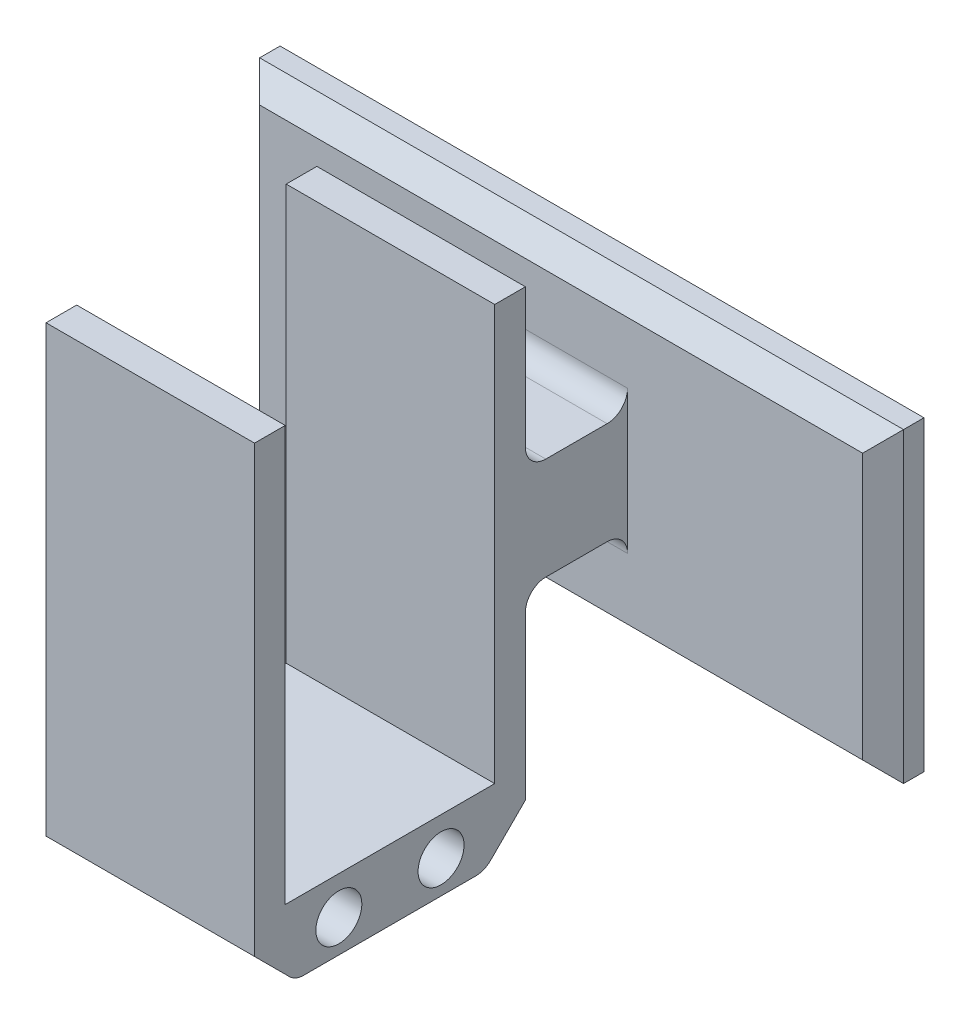
SolidWorks part; units mm, degrees
material "PLA"
ref_plane "Front Plane" through (0, 0, 0) normal (0, 0, 1) x (1, 0, 0)
ref_plane "Top Plane" through (0, 0, 0) normal (0, 1, 0) x (1, 0, 0)
ref_plane "Right Plane" through (0, 0, 0) normal (1, 0, 0) x (0, 0, -1)
sketch "Sketch1" plane through (0, 0, 0) normal (1, 0, 0) x (0, 0, -1)
  line L0 (-10.25, 20.3) -> (10.25, 20.3)
  line L1 (-10.25, -20.3) -> (10.25, -20.3)
  line L2 (-10.25, -20.3) -> (-10.25, 20.3)
  line L4 (10.25, -20.3) -> (10.25, 20.3)
  line L5 (-10.25, -20.3) -> (-13.25, -20.3)
  line L6 (-13.25, -20.3) -> (-13.25, 29.7)
  line L7 (-13.25, 29.7) -> (13.25, 29.7)
  line L8 (10.25, -20.3) -> (13.25, -20.3)
  line L11 (-10.05, 20.1) -> (10.05, 20.1)
  line L13 (13.25, -20.3) -> (13.25, 29.7)
  point P5 (0, 20.3)
  point P6 (-10.25, 0)
  line B0 (-8.8772, 20.1) -> (-10.8742, 20.1) construction
  line B1 (7.4, 20.1) -> (11.2713, 20.1) construction
  line B2 (10.05, 18.0597) -> (10.05, 22.3295) construction
  line B3 (-3.2, -20.1) -> (-12.1258, -20.1) construction
  line B4 (-10.05, -15.1145) -> (-10.05, -21.3251) construction
  line B5 (-10.05, -20.1) -> (10.05, -20.1)
  line B6 (-10.05, -20.1) -> (-10.05, 20.1)
  line B7 (10.05, -20.1) -> (10.05, 20.1)
  circle B8 centre (-5, 24) radius 2.25
  circle B9 centre (5, 24) radius 2.25
  dimension "D1" = 0.2
  dimension "D2" = 0.2
  dimension "D3" = 0.2
  dimension "D4" = 0.2
  dimension "D5" = 3
  dimension "D6" = 50
  dimension "D7" = 3
sketch_block_instance "Block1-1"
sketch_block "Block1"
extrude "Boss-Extrude1" add sketch "Sketch1" along normal blind 20 contours L8 L13 L7 L6 L5 L2 L0 L4 B9 B8
sketch "Sketch2" plane through (0, 0, 0) normal (-1, 0, 0) x (0, 0, 1)
  circle A0 centre (-5, 24) radius 2.25
  circle A1 centre (5, 24) radius 2.25
extrude "Boss-Extrude2" add sketch "Sketch2" against normal blind 10
sketch "Sketch4" plane through (20, 0, 0) normal (1, 0, 0) x (0, 0, -1)
  line L0 (13.25, -20.3) -> (13.25, 29.7) construction
  line L1 (-13.25, 29.7) -> (13.25, 29.7)
  line L2 (-13.25, 29.7) -> (-13.25, 27.2)
  line L3 (-13.25, 27.2) -> (13.25, 27.2)
  line L4 (13.25, 29.7) -> (13.25, 27.2)
  dimension "D1" = 2.5
extrude "Cut-Extrude1" cut sketch "Sketch4" against normal through all
chamfer "Chamfer2" distance 4 angle 45 1 edges at (10, 27.2, -13.25)
chamfer "Chamfer3" distance 4 angle 45 1 edges at (10, 27.2, 13.25)
fillet "Fillet4" radius 2 2 edges at (10, 27.2, -9.25) (10, 27.2, 9.25)
sketch "Sketch7" plane through (20, 0, 0) normal (1, 0, 0) x (0, 0, -1)
  line L0 (13.25, -20.3) -> (13.25, 23.2) construction
  line L3 (23.25, -5.3) -> (13.25, -5.3)
  line L6 (13.25, 4.7) -> (23.25, 4.7)
  line L8 (23.25, 4.7) -> (23.25, -5.3)
  line L9 (13.25, 4.7) -> (13.25, -5.3)
  line L10 (10.25, -20.3) -> (13.25, -20.3) construction
  dimension "D1" = 10
  dimension "D2" = 15
extrude "Boss-Extrude5" add sketch "Sketch7" against normal up to surface (20 mm away) up to face at (0, 9.4758, 0)
fillet "Fillet6" radius 2 2 edges at (10, 4.7, -13.25) (10, -5.3, -13.25)
sketch "Sketch8" plane through (0, 0, -23.25) normal (0, 0, -1) x (-1, 0, 0)
  line L1 (-45.4, 14.7) -> (17.6, 14.7)
  line L2 (-45.4, 14.7) -> (-45.4, -15.3)
  line L3 (-45.4, -15.3) -> (17.6, -15.3)
  line L4 (17.6, 14.7) -> (17.6, -15.3)
  line L5 (0, 4.7) -> (-20, 4.7) construction
  line L7 (-13.9, 4.7) -> (-13.9, -5.3) construction
  line L8 (-20, -5.3) -> (-20, 4.7) construction
  line L9 (-20, -0.3) -> (0, -0.3) construction
  line L10 (0, 4.7) -> (0, -5.3) construction
  line L11 (0, -5.3) -> (-20, -5.3) construction
  point P10 (-13.9, 14.7)
  point P17 (-45.4, -0.3)
  dimension "D1" = 63
  dimension "D2" = 30
  dimension "D3" = 6.1
extrude "Boss-Extrude6" add sketch "Sketch8" along normal blind 4
chamfer "Chamfer4" distance 2 angle 45 4 edges at (-17.6, -0.3, -23.25) (13.9, -15.3, -23.25) (45.4, -0.3, -23.25) (13.9, 14.7, -23.25)
fillet "Fillet7" radius 2 2 edges at (10, 4.7, -23.25) (10, -5.3, -23.25)
ref_plane "Plane2" through (20, 20.3, 10.25) normal (0, 0, -1) x (-1, 0, 0)
sketch "Sketch12" plane through (20, 0, 0) normal (1, 0, 0) x (0, 0, -1)
  line L0 (13.25, 23.2) -> (9.8358, 26.6142) construction
  line L1 (-8.4216, 27.2) -> (8.4216, 27.2) construction
  line L2 (-9.8358, 26.6142) -> (-13.25, 23.2) construction
  line L3 (13.25, 23.2) -> (9.8358, 26.6142)
  line L4 (-8.4216, 27.2) -> (8.4216, 27.2)
  line L5 (-9.8358, 26.6142) -> (-13.25, 23.2)
  line L6 (0, 20.3) -> (-13.25, 20.3) construction
  line L7 (-10.25, 20.3) -> (10.25, 20.3) construction
  line L8 (-13.25, -20.3) -> (-13.25, 23.2) construction
  line L9 (-13.25, 20.3) -> (13.25, 20.3)
  line L10 (13.25, 6.7) -> (13.25, 23.2) construction
  line L11 (13.25, 20.3) -> (13.25, 23.2)
  line L12 (-13.25, 20.3) -> (-13.25, 23.2)
  arc A0 (9.8358, 26.6142) -> (8.4216, 27.2) centre (8.4216, 25.2) ccw construction
  arc A1 (-8.4216, 27.2) -> (-9.8358, 26.6142) centre (-8.4216, 25.2) ccw construction
  arc A2 (9.8358, 26.6142) -> (8.4216, 27.2) centre (8.4216, 25.2) ccw
  arc A3 (-8.4216, 27.2) -> (-9.8358, 26.6142) centre (-8.4216, 25.2) ccw
sketch "Sketch13" plane through (20, 0, 0) normal (1, 0, 0) x (0, 0, -1)
  line B0 (-13.25, -23.2) -> (-9.8358, -26.6142)
  line B1 (8.4216, -27.2) -> (-8.4216, -27.2)
  line B2 (9.8358, -26.6142) -> (13.25, -23.2)
  line B3 (0, -20.3) -> (13.25, -20.3) construction
  line B4 (13.25, -20.3) -> (-13.25, -20.3)
  line B5 (-13.25, -20.3) -> (-13.25, -23.2)
  line B6 (13.25, -20.3) -> (13.25, -23.2)
  arc B7 (-9.8358, -26.6142) -> (-8.4216, -27.2) centre (-8.4216, -25.2) ccw
  arc B8 (8.4216, -27.2) -> (9.8358, -26.6142) centre (8.4216, -25.2) ccw
  circle B9 centre (5, -24) radius 2.25
  circle B10 centre (-5, -24) radius 2.25
sketch_block_instance "Block2-1"
sketch_block "Block2"
extrude "Boss-Extrude8" add sketch "Sketch13" against normal up to surface (20 mm away) up to face at (0, 5.5655, -7.3)
extrude "Cut-Extrude2" cut sketch "Sketch12" against normal through all
sketch "Sketch14" plane through (0, 0, 0) normal (-1, 0, 0) x (0, 0, 1)
  circle A0 centre (-5, -24) radius 2.25
  circle A1 centre (5, -24) radius 2.25
extrude "Boss-Extrude9" add sketch "Sketch14" against normal blind 10
sketch "Sketch15" plane through (20, 0, 0) normal (1, 0, 0) x (0, 0, -1)
  line L14 (-10.25, 20.3) -> (-13.25, 20.3)
  line L15 (-13.25, 20.3) -> (-13.25, -23.2)
  line L16 (-13.25, -23.2) -> (-9.8358, -26.6142)
  line L17 (-8.4216, -27.2) -> (8.4216, -27.2)
  line L18 (9.8358, -26.6142) -> (13.25, -23.2)
  line L19 (13.25, -23.2) -> (13.25, -7.3)
  line L20 (15.25, -5.3) -> (21.25, -5.3)
  line L21 (23.25, -7.3) -> (23.25, 6.7)
  line L22 (21.25, 4.7) -> (15.25, 4.7)
  line L23 (13.25, 6.7) -> (13.25, 20.3)
  line L24 (13.25, 20.3) -> (10.25, 20.3)
  line L25 (10.25, 20.3) -> (10.25, -20.3)
  line L26 (10.25, -20.3) -> (-10.25, -20.3)
  line L27 (-10.25, -20.3) -> (-10.25, 20.3)
  line L28 (-10.25, 20.3) -> (-13.25, 20.3)
  line L29 (-13.25, 20.3) -> (-13.25, -23.2)
  line L30 (-13.25, -23.2) -> (-9.8358, -26.6142)
  line L31 (-8.4216, -27.2) -> (8.4216, -27.2)
  line L32 (9.8358, -26.6142) -> (13.25, -23.2)
  line L33 (13.25, -23.2) -> (13.25, -7.3)
  line L34 (15.25, -5.3) -> (21.25, -5.3)
  line L35 (23.25, -7.3) -> (23.25, 6.7)
  line L36 (21.25, 4.7) -> (15.25, 4.7)
  line L37 (13.25, 6.7) -> (13.25, 20.3)
  line L38 (13.25, 20.3) -> (10.25, 20.3)
  line L39 (10.25, 20.3) -> (10.25, -20.3)
  line L40 (10.25, -20.3) -> (-10.25, -20.3)
  line L41 (-10.25, -20.3) -> (-10.25, 20.3)
  circle A0 centre (5, -24) radius 2.25 construction
  circle A1 centre (-5, -24) radius 2.25 construction
  circle A2 centre (5, -24) radius 2.25
  circle A3 centre (-5, -24) radius 2.25
  arc A6 (-9.8358, -26.6142) -> (-8.4216, -27.2) centre (-8.4216, -25.2) ccw
  arc A7 (8.4216, -27.2) -> (9.8358, -26.6142) centre (8.4216, -25.2) ccw
  arc A8 (15.25, -5.3) -> (13.25, -7.3) centre (15.25, -7.3) ccw
  arc A9 (23.25, -7.3) -> (21.25, -5.3) centre (21.25, -7.3) ccw
  arc A10 (21.25, 4.7) -> (23.25, 6.7) centre (21.25, 6.7) ccw
  arc A11 (13.25, 6.7) -> (15.25, 4.7) centre (15.25, 6.7) ccw
  arc A12 (-9.8358, -26.6142) -> (-8.4216, -27.2) centre (-8.4216, -25.2) ccw
  arc A13 (8.4216, -27.2) -> (9.8358, -26.6142) centre (8.4216, -25.2) ccw
  arc A14 (15.25, -5.3) -> (13.25, -7.3) centre (15.25, -7.3) ccw
  arc A15 (23.25, -7.3) -> (21.25, -5.3) centre (21.25, -7.3) ccw
  arc A16 (21.25, 4.7) -> (23.25, 6.7) centre (21.25, 6.7) ccw
  arc A17 (13.25, 6.7) -> (15.25, 4.7) centre (15.25, 6.7) ccw
  dimension "D1" = 0
extrude "Boss-Extrude10" add sketch "Sketch15" along normal blind 0.4
